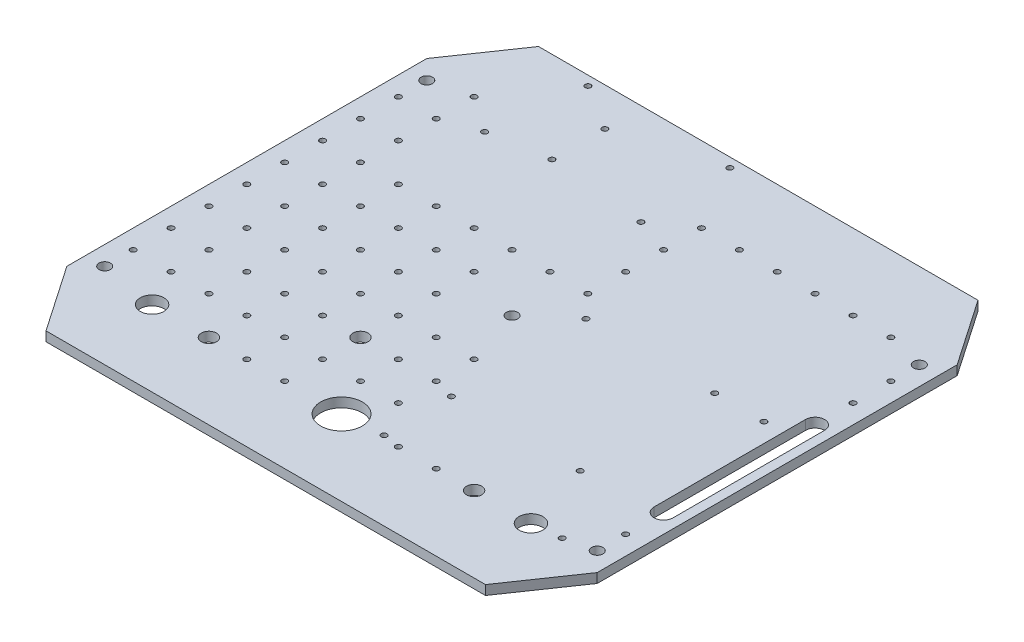
SolidWorks part; units mm, degrees
ref_plane "Plan de face" through (0, 0, 0) normal (0, 0, 1) x (1, 0, 0)
ref_plane "Plan de dessus" through (0, 0, 0) normal (0, 1, 0) x (1, 0, 0)
ref_plane "Plan de droite" through (0, 0, 0) normal (1, 0, 0) x (0, 0, -1)
sketch "Esquisse1" plane through (0, 0, 0) normal (0, 1, 0) x (1, 0, 0)
  line L0 (0, 0) -> (-140, 0) construction
  line L1 (0, 0) -> (0, 130) construction
  line L2 (-140, -95) -> (-140, 95)
  line L3 (-140, 95) -> (-116, 130)
  line L4 (-116, 130) -> (116, 130)
  line L5 (-116, -130) -> (116, -130)
  line L6 (-140, -95) -> (-116, -130)
  line L7 (140, -95) -> (116, -130)
  line L8 (140, 95) -> (116, 130)
  line L9 (140, -95) -> (140, 95)
  line L10 (130, 30) -> (130, -50) construction
  line L11 (135, 30) -> (135, -50)
  line L12 (125, 30) -> (125, -50)
  circle A0 centre (-130, 85) radius 3
  circle A1 centre (-30, 10) radius 1.5
  circle A2 centre (-50, 10) radius 1.5
  circle A3 centre (-70, 10) radius 1.5
  circle A4 centre (-90, 10) radius 1.5
  circle A5 centre (-110, 10) radius 1.5
  circle A6 centre (-130, 10) radius 1.5
  circle A7 centre (-50, 30) radius 1.5
  circle A8 centre (-70, 30) radius 1.5
  circle A9 centre (-90, 30) radius 1.5
  circle A10 centre (-110, 30) radius 1.5
  circle A11 centre (-130, 30) radius 1.5
  circle A12 centre (-100, -90) radius 6.25
  circle A13 centre (100, -90) radius 6.25
  circle A14 centre (-70, -90) radius 4
  circle A15 centre (-110, 50) radius 1.5
  circle A16 centre (-130, 50) radius 1.5
  circle A17 centre (-30, -50) radius 4
  circle A18 centre (70, -90) radius 4
  circle A20 centre (-110, 70) radius 1.5
  circle A21 centre (-130, 70) radius 1.5
  circle A25 centre (-110, 90) radius 1.5
  circle A27 centre (-30, 30) radius 1.5
  circle A31 centre (-10, 30) radius 1.5
  circle A34 centre (-10, 125) radius 1.5
  circle A35 centre (-130, 90) radius 1.5 [skipped]
  circle A36 centre (-10, -70) radius 1.5
  circle A37 centre (-10, -50) radius 1.5
  circle A38 centre (-10, -30) radius 1.5
  circle A39 centre (-30, -90) radius 1.5
  circle A40 centre (-30, -70) radius 1.5
  circle A42 centre (-30, -30) radius 1.5
  circle A43 centre (-84.9, 125) radius 1.5
  circle A44 centre (-60.8, 109.8) radius 1.5
  circle A46 centre (-50, -90) radius 1.5
  circle A47 centre (-130, -70) radius 1.5
  circle A48 centre (-110, -70) radius 1.5
  circle A49 centre (-90, -70) radius 1.5
  circle A50 centre (-70, -70) radius 1.5
  circle A51 centre (-50, -70) radius 1.5
  circle A52 centre (-130, -50) radius 1.5
  circle A53 centre (-110, -50) radius 1.5
  circle A54 centre (-90, -50) radius 1.5
  circle A55 centre (-70, -50) radius 1.5
  circle A56 centre (-50, -50) radius 1.5
  circle A57 centre (-130, -30) radius 1.5
  circle A58 centre (-110, -30) radius 1.5
  circle A59 centre (-90, -30) radius 1.5
  circle A60 centre (-70, -30) radius 1.5
  circle A61 centre (-50, -30) radius 1.5
  circle A62 centre (-130, -10) radius 1.5
  circle A63 centre (-110, -10) radius 1.5
  circle A64 centre (-90, -10) radius 1.5
  circle A65 centre (-70, -10) radius 1.5
  circle A66 centre (-50, -10) radius 1.5
  circle A67 centre (-30, -10) radius 1.5
  circle A68 centre (-130, -85) radius 3
  circle A69 centre (130, -85) radius 3
  circle A70 centre (21, -88.5) radius 1.5
  circle A71 centre (115, -88.5) radius 1.5
  circle A72 centre (21, -53) radius 1.5
  circle A73 centre (89, -53) radius 1.5
  circle A74 centre (21, 18) radius 1.5
  arc A75 (135, 30) -> (125, 30) centre (130, 30) ccw
  circle A76 centre (89, 18) radius 1.5
  circle A77 centre (115, 18) radius 1.5
  arc A78 (125, -50) -> (135, -50) centre (130, -50) ccw
  circle A79 centre (0, -90) radius 11
  circle A81 centre (-60.8, 81.9) radius 1.5
  circle A82 centre (-91.22, 76.78) radius 1.5
  circle A83 centre (-8.7, 76.78) radius 1.5
  circle A90 centre (130, -70) radius 1.5
  circle A91 centre (50, -90) radius 1.5
  circle A98 centre (30, -90) radius 1.5
  circle A99 centre (10, -30) radius 1.5
  circle A100 centre (10, -50) radius 1.5
  circle A101 centre (10, -70) radius 1.5
  circle A102 centre (10, 90) radius 1.5
  circle A103 centre (10, 70) radius 1.5
  circle A104 centre (10, 50) radius 1.5
  circle A105 centre (10, 30) radius 1.5
  circle A106 centre (30, 90) radius 1.5
  circle A111 centre (110, 90) radius 1.5
  circle A112 centre (90, 90) radius 1.5
  circle A113 centre (70, 90) radius 1.5
  circle A114 centre (50, 90) radius 1.5
  circle A115 centre (130, 70) radius 1.5
  circle A120 centre (130, 50) radius 1.5
  circle A136 centre (130, 85) radius 3
  circle A137 centre (0, 0) radius 3
  circle A139 centre (-90, 50) radius 1.5 [skipped]
  circle A140 centre (-70, 50) radius 1.5 [skipped]
  circle A141 centre (-70, 70) radius 1.5 [skipped]
  circle A142 centre (-70, 90) radius 1.5 [skipped]
  circle A143 centre (-90, 70) radius 1.5 [skipped]
  circle A144 centre (-90, 90) radius 1.5 [skipped]
  circle A145 centre (-50, 50) radius 1.5 [skipped]
  circle A146 centre (-50, 70) radius 1.5 [skipped]
  circle A147 centre (-50, 90) radius 1.5 [skipped]
  circle A148 centre (-30, 50) radius 1.5 [skipped]
  circle A149 centre (-30, 70) radius 1.5 [skipped]
  circle A150 centre (-30, 90) radius 1.5 [skipped]
  point P149 (0, -130)
  point P167 (130, -10)
  dimension "D1" = 140
  dimension "D5" = 30
  dimension "D10" = 6
  dimension "D8" = 3
  dimension "D13" = 6
  dimension "D17" = 6
  dimension "D18" = 3
  dimension "D25" = 5
  dimension "D27" = 22
  dimension "D29" = 20
  dimension "D31" = 10
  dimension "D32" = 3
  dimension "D30" = 12.5
  dimension "D46" = 8
  dimension "D2" = 68
  dimension "D3" = 95
  dimension "D4" = 24
  dimension "D6" = 10
  dimension "D7" = 10
  dimension "D9" = 10
  dimension "D11" = 5
  dimension "D12" = 2
  dimension "D14" = 10
  dimension "D15" = 50
  dimension "D16" = 30
  dimension "D19" = 94
  dimension "D20" = 35.5
  dimension "D21" = 106.5
  dimension "D22" = 41.5
  dimension "D23" = 119
  dimension "D24" = 260
  dimension "D26" = 80
  dimension "D28" = 90
  dimension "D33" = 5
  dimension "D34" = 10
  dimension "D35" = 24.1
  dimension "D36" = 1.3
  dimension "D37" = 48.22
  dimension "D38" = 27.9
  dimension "D39" = 15.2
  dimension "D40" = 82.52
  dimension "D41" = 52.1
  dimension "D42" = 20
  dimension "D43" = 20
  dimension "D44" = 20
  dimension "D45" = 20
extrude "Boss.-Extru.1" add sketch "Esquisse1" along normal blind 5
